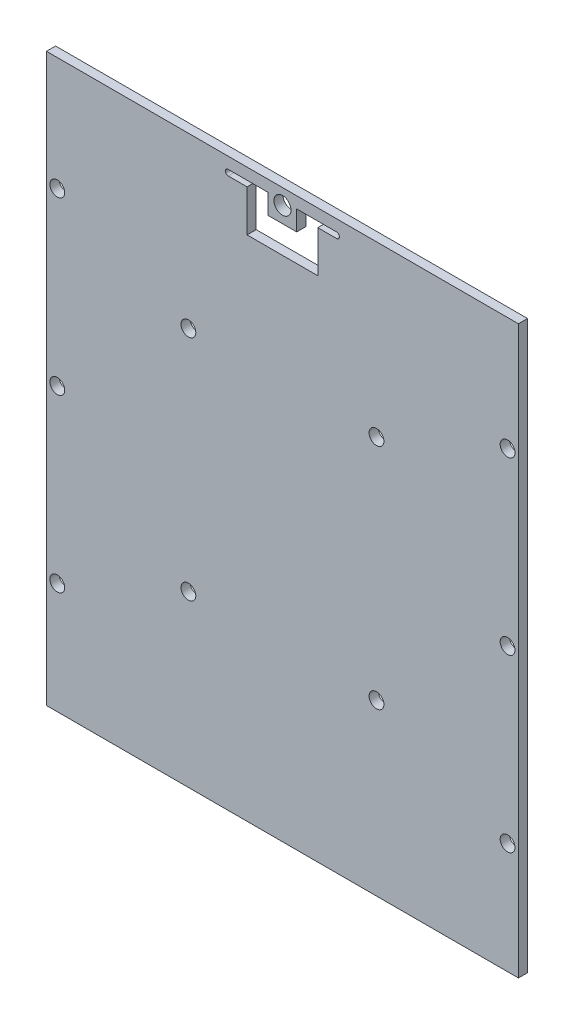
SolidWorks part; units mm, degrees
material "FR4_stuffedProtoboard"
ref_plane "Front Plane" through (0, 0, 0) normal (0, 0, 1) x (1, 0, 0)
ref_plane "Top Plane" through (0, 0, 0) normal (0, 1, 0) x (1, 0, 0)
ref_plane "Right Plane" through (0, 0, 0) normal (1, 0, 0) x (0, 0, -1)
sketch "Sketch1" plane through (0, 0, 0) normal (0, 0, 1) x (1, 0, 0)
  line L0 (-37, -97) -> (37, -97) construction
  line L5 (-37, -95.4) -> (37, -95.4) construction
  line L6 (-37, -87) -> (37, -87) construction
  line L7 (-37, -85.4) -> (37, -85.4) construction
  line L8 (-37, -77) -> (37, -77) construction
  line L9 (-37, -75.4) -> (37, -75.4) construction
  line L10 (-37, -67) -> (37, -67) construction
  line L11 (-37, -65.4) -> (37, -65.4) construction
  line L12 (-37, -57) -> (37, -57) construction
  line L13 (-37, -55.4) -> (37, -55.4) construction
  line L14 (-37, -47) -> (37, -47) construction
  line L15 (-37, -45.4) -> (37, -45.4) construction
  line L16 (-37, -37) -> (37, -37) construction
  line L17 (-37, -35.4) -> (37, -35.4) construction
  line L18 (-37, -27) -> (37, -27) construction
  line L19 (-37, -25.4) -> (37, -25.4) construction
  line L20 (-37, -17) -> (37, -17) construction
  line L21 (-37, -15.4) -> (37, -15.4) construction
  line L22 (-37, 15.4) -> (37, 15.4) construction
  line L23 (-37, 17) -> (37, 17) construction
  line L24 (-37, 25.4) -> (37, 25.4) construction
  line L25 (-37, 27) -> (37, 27) construction
  line L26 (-37, 35.4) -> (37, 35.4) construction
  line L27 (-37, 37) -> (37, 37) construction
  line L29 (-41.5, 107) -> (41.5, 107)
  line L30 (-41.5, 107) -> (-41.5, -107)
  line L31 (-41.5, -107) -> (41.5, -107)
  line L33 (41.5, 107) -> (41.5, -107)
  line L35 (-26.7, 107) -> (-28.3, 107) construction
  line L37 (-41.5, 109.5) -> (-41.5, 97.4) construction
  line L38 (41.5, 112.5) -> (41.5, 109.5) construction
  line L39 (-28.3, -107) -> (-26.7, -107) construction
  line L40 (-41.4, 106.9) -> (41.4, 106.9)
  line L41 (41.4, 106.9) -> (41.4, -106.9)
  line L42 (-41.4, -106.9) -> (41.4, -106.9)
  line L43 (-41.4, 106.9) -> (-41.4, -106.9)
  line L76 (-37, 45.4) -> (37, 45.4) construction
  line L77 (-37, 47) -> (37, 47) construction
  line L78 (-37, 55.4) -> (37, 55.4) construction
  line L79 (-37, 57) -> (37, 57) construction
  line L80 (-37, 65.4) -> (37, 65.4) construction
  line L81 (-37, 67) -> (37, 67) construction
  line L82 (-37, 75.4) -> (37, 75.4) construction
  line L83 (-37, 77) -> (37, 77) construction
  line L84 (-37, 85.4) -> (37, 85.4) construction
  line L85 (-37, 87) -> (37, 87) construction
  line L86 (-37, 95.4) -> (37, 95.4) construction
  line L87 (-37, 97) -> (37, 97) construction
  line L88 (-37, -97) -> (37, -97) construction
  line L89 (-37, -95.4) -> (37, -95.4) construction
  line L90 (-37, -87) -> (37, -87) construction
  line L91 (-37, -85.4) -> (37, -85.4) construction
  line L92 (-37, -77) -> (37, -77) construction
  line L93 (-37, -75.4) -> (37, -75.4) construction
  line L94 (-37, -67) -> (37, -67) construction
  line L95 (-37, -65.4) -> (37, -65.4) construction
  line L96 (-37, -57) -> (37, -57) construction
  line L97 (-37, -55.4) -> (37, -55.4) construction
  line L98 (-37, -47) -> (37, -47) construction
  line L99 (-37, -45.4) -> (37, -45.4) construction
  line L100 (-37, -37) -> (37, -37) construction
  line L101 (-37, -35.4) -> (37, -35.4) construction
  line L102 (-37, -27) -> (37, -27) construction
  line L103 (-37, -25.4) -> (37, -25.4) construction
  line L104 (-37, -17) -> (37, -17) construction
  line L105 (-37, -15.4) -> (37, -15.4) construction
  line L106 (-37, 15.4) -> (37, 15.4) construction
  line L107 (-37, 17) -> (37, 17) construction
  line L108 (-37, 25.4) -> (37, 25.4) construction
  line L109 (-37, 27) -> (37, 27) construction
  line L110 (-37, 35.4) -> (37, 35.4) construction
  line L111 (-37, 37) -> (37, 37) construction
  line L112 (-37, 45.4) -> (37, 45.4) construction
  line L113 (-37, 47) -> (37, 47) construction
  line L114 (-37, 55.4) -> (37, 55.4) construction
  line L115 (-37, 57) -> (37, 57) construction
  line L116 (-37, 65.4) -> (37, 65.4) construction
  line L117 (-37, 67) -> (37, 67) construction
  line L118 (-37, 75.4) -> (37, 75.4) construction
  line L119 (-37, 77) -> (37, 77) construction
  line L120 (-37, 85.4) -> (37, 85.4) construction
  line L121 (-37, 87) -> (37, 87) construction
  line L122 (-37, 95.4) -> (37, 95.4) construction
  line L123 (-37, 97) -> (37, 97) construction
  circle A0 centre (-39.5, 87) radius 0.8 construction
  circle A1 centre (-39.5, -27) radius 0.8 construction
  circle A2 centre (-39.5, 57) radius 0.8 construction
  circle A3 centre (39.5, -27) radius 0.8 construction
  circle A4 centre (-39.5, -27) radius 0.8
  circle A5 centre (-39.5, 27) radius 0.8 construction
  circle A8 centre (39.5, -27) radius 0.8
  circle A11 centre (-39.5, -57) radius 0.8 construction
  circle A13 centre (-39.5, -87) radius 0.8 construction
  circle A16 centre (0, -104.2) radius 0.8 construction
  circle A19 centre (39.5, -87) radius 0.8 construction
  circle A21 centre (39.5, -57) radius 0.8 construction
  circle A27 centre (39.5, 27) radius 0.8 construction
  circle A30 centre (39.5, 57) radius 0.8 construction
  circle A32 centre (39.5, 87) radius 0.8 construction
  circle A35 centre (0, 104.2) radius 0.8 construction
  circle A38 centre (-39.5, 87) radius 0.8
  circle A40 centre (-39.5, 57) radius 0.8
  circle A43 centre (-39.5, 27) radius 0.8
  circle A49 centre (-39.5, -57) radius 0.8
  circle A51 centre (-39.5, -87) radius 0.8
  circle A54 centre (0, -104.2) radius 0.8
  circle A57 centre (39.5, -87) radius 0.8
  circle A59 centre (39.5, -57) radius 0.8
  circle A65 centre (39.5, 27) radius 0.8
  circle A68 centre (39.5, 57) radius 0.8
  circle A70 centre (39.5, 87) radius 0.8
  circle A73 centre (0, 104.2) radius 0.8
  dimension "D1" = 0.1
extrude "pcb extrude" add sketch "Sketch1" along normal blind 1.6
sketch "Sketch7" plane through (0, 0, 1.6) normal (0, 0, 1) x (1, 0, 0)
  line L0 (-41.4, 106.9) -> (41.4, 106.9) construction
  line L1 (-41.25, 106.9) -> (-41.4, 106.9)
  line L2 (-41.25, 106.75) -> (-41.25, -106.75)
  line L3 (-41.25, -106.9) -> (-41.4, -106.9)
  line L4 (-41.4, 106.9) -> (-41.4, -106.9)
  line L5 (-41.4, -106.9) -> (41.4, -106.9) construction
  line L6 (-41.4, 106.9) -> (-41.4, -106.9) construction
  line L7 (0, -55) -> (0, 55) construction
  line L8 (41.25, -106.9) -> (41.4, -106.9)
  line L9 (41.4, 106.9) -> (41.4, -106.9)
  line L10 (41.25, 106.9) -> (41.4, 106.9)
  line L11 (41.25, 106.75) -> (41.25, -106.75)
  line L12 (55, 0) -> (-55, 0) construction
  line L13 (-41.25, -106.9) -> (41.25, -106.9)
  line L15 (-41.25, -106.75) -> (41.25, -106.75)
  line L17 (-41.25, 106.75) -> (41.25, 106.75)
  line L19 (-41.25, 106.9) -> (41.25, 106.9)
  dimension "D1" = 0.15
  dimension "D2" = 0.15
  dimension "D3" = 0.15
  dimension "D4" = 0.15
extrude "Offset Edges" [suppressed] cut sketch "Sketch7" against normal up to surface (1.6 mm away)
sketch "connector locations" plane through (0, 0, 1.6) normal (0, 0, 1) x (1, 0, 0)
  line L0 (-37, 97) -> (37, 97) construction
  line L1 (-33.9182, 100.556) -> (-9.2802, 100.556)
  line L2 (-33.9182, 100.556) -> (-33.9182, 99.159)
  line L3 (-33.9182, 99.159) -> (-9.2802, 99.159)
  line L4 (-9.2802, 100.556) -> (-9.2802, 99.159)
  line L5 (-33.9182, 100.556) -> (-9.2802, 99.159) construction
  line L6 (-33.9182, 99.159) -> (-9.2802, 100.556) construction
  line L7 (-37, 87) -> (37, 87) construction
  line L8 (-33.9182, 90.556) -> (-22.0818, 90.556)
  line L9 (-33.9182, 90.556) -> (-33.9182, 89.159)
  line L10 (-33.9182, 89.159) -> (-22.0818, 89.159)
  line L11 (-22.0818, 90.556) -> (-22.0818, 89.159)
  line L12 (-33.9182, 90.556) -> (-22.0818, 89.159) construction
  line L13 (-33.9182, 89.159) -> (-22.0818, 90.556) construction
  line L14 (0, -0.88) -> (0, 0.88) construction
  line L15 (-12.319, 90.556) -> (12.319, 90.556)
  line L16 (-12.319, 90.556) -> (-12.319, 89.159)
  line L17 (-12.319, 89.159) -> (12.319, 89.159)
  line L18 (12.319, 90.556) -> (12.319, 89.159)
  line L19 (-12.319, 90.556) -> (12.319, 89.159) construction
  line L20 (-12.319, 89.159) -> (12.319, 90.556) construction
  line L21 (-37, -85.4) -> (37, -85.4) construction
  line L22 (-33.9182, -91.844) -> (-9.2802, -91.844)
  line L23 (-33.9182, -91.844) -> (-33.9182, -93.241)
  line L24 (-33.9182, -93.241) -> (-9.2802, -93.241)
  line L25 (-9.2802, -91.844) -> (-9.2802, -93.241)
  line L26 (-33.9182, -91.844) -> (-9.2802, -93.241) construction
  line L27 (-33.9182, -93.241) -> (-9.2802, -91.844) construction
  line L28 (-33.9182, -81.844) -> (-22.0818, -81.844)
  line L29 (-33.9182, -81.844) -> (-33.9182, -83.241)
  line L30 (-33.9182, -83.241) -> (-22.0818, -83.241)
  line L31 (-22.0818, -81.844) -> (-22.0818, -83.241)
  line L32 (-33.9182, -81.844) -> (-22.0818, -83.241) construction
  line L33 (-33.9182, -83.241) -> (-22.0818, -81.844) construction
  line L34 (-12.319, -81.844) -> (12.319, -81.844)
  line L35 (-12.319, -81.844) -> (-12.319, -83.241)
  line L36 (-12.319, -83.241) -> (12.319, -83.241)
  line L37 (12.319, -81.844) -> (12.319, -83.241)
  line L38 (-12.319, -81.844) -> (12.319, -83.241) construction
  line L39 (-12.319, -83.241) -> (12.319, -81.844) construction
  line L40 (-37, -95.4) -> (37, -95.4) construction
  line L41 (-33.9182, 80.556) -> (-33.9182, 79.159)
  line L42 (-33.9182, 80.556) -> (-22.0818, 80.556)
  line L43 (-22.0818, 80.556) -> (-22.0818, 79.159)
  line L44 (-33.9182, 79.159) -> (-22.0818, 79.159)
  line L45 (-33.9182, 80.556) -> (-22.0818, 79.159) construction
  line L46 (-33.9182, 79.159) -> (-22.0818, 80.556) construction
  line L47 (-12.319, 80.556) -> (-12.319, 79.159)
  line L48 (-12.319, 80.556) -> (12.319, 80.556)
  line L49 (12.319, 80.556) -> (12.319, 79.159)
  line L50 (-12.319, 79.159) -> (12.319, 79.159)
  line L51 (-12.319, 80.556) -> (12.319, 79.159) construction
  line L52 (-12.319, 79.159) -> (12.319, 80.556) construction
  line L53 (-33.9182, 70.556) -> (-33.9182, 69.159)
  line L54 (-33.9182, 70.556) -> (-22.0818, 70.556)
  line L55 (-22.0818, 70.556) -> (-22.0818, 69.159)
  line L56 (-33.9182, 69.159) -> (-22.0818, 69.159)
  line L57 (-33.9182, 70.556) -> (-22.0818, 69.159) construction
  line L58 (-33.9182, 69.159) -> (-22.0818, 70.556) construction
  line L59 (-12.319, 70.556) -> (-12.319, 69.159)
  line L60 (-12.319, 70.556) -> (12.319, 70.556)
  line L61 (12.319, 70.556) -> (12.319, 69.159)
  line L62 (-12.319, 69.159) -> (12.319, 69.159)
  line L63 (-12.319, 70.556) -> (12.319, 69.159) construction
  line L64 (-12.319, 69.159) -> (12.319, 70.556) construction
  line L65 (-33.9182, 60.556) -> (-33.9182, 59.159)
  line L66 (-33.9182, 60.556) -> (-22.0818, 60.556)
  line L67 (-22.0818, 60.556) -> (-22.0818, 59.159)
  line L68 (-33.9182, 59.159) -> (-22.0818, 59.159)
  line L69 (-33.9182, 60.556) -> (-22.0818, 59.159) construction
  line L70 (-33.9182, 59.159) -> (-22.0818, 60.556) construction
  line L71 (-12.319, 60.556) -> (-12.319, 59.159)
  line L72 (-12.319, 60.556) -> (12.319, 60.556)
  line L73 (12.319, 60.556) -> (12.319, 59.159)
  line L74 (-12.319, 59.159) -> (12.319, 59.159)
  line L75 (-12.319, 60.556) -> (12.319, 59.159) construction
  line L76 (-12.319, 59.159) -> (12.319, 60.556) construction
  line L77 (-33.9182, 50.556) -> (-33.9182, 49.159)
  line L78 (-33.9182, 50.556) -> (-22.0818, 50.556)
  line L79 (-22.0818, 50.556) -> (-22.0818, 49.159)
  line L80 (-33.9182, 49.159) -> (-22.0818, 49.159)
  line L81 (-33.9182, 50.556) -> (-22.0818, 49.159) construction
  line L82 (-33.9182, 49.159) -> (-22.0818, 50.556) construction
  line L83 (-12.319, 50.556) -> (-12.319, 49.159)
  line L84 (-12.319, 50.556) -> (12.319, 50.556)
  line L85 (12.319, 50.556) -> (12.319, 49.159)
  line L86 (-12.319, 49.159) -> (12.319, 49.159)
  line L87 (-12.319, 50.556) -> (12.319, 49.159) construction
  line L88 (-12.319, 49.159) -> (12.319, 50.556) construction
  line L89 (-33.9182, 40.556) -> (-33.9182, 39.159)
  line L90 (-33.9182, 40.556) -> (-22.0818, 40.556)
  line L91 (-22.0818, 40.556) -> (-22.0818, 39.159)
  line L92 (-33.9182, 39.159) -> (-22.0818, 39.159)
  line L93 (-33.9182, 40.556) -> (-22.0818, 39.159) construction
  line L94 (-33.9182, 39.159) -> (-22.0818, 40.556) construction
  line L95 (-12.319, 40.556) -> (-12.319, 39.159)
  line L96 (-12.319, 40.556) -> (12.319, 40.556)
  line L97 (12.319, 40.556) -> (12.319, 39.159)
  line L98 (-12.319, 39.159) -> (12.319, 39.159)
  line L99 (-12.319, 40.556) -> (12.319, 39.159) construction
  line L100 (-12.319, 39.159) -> (12.319, 40.556) construction
  line L101 (-33.9182, 30.556) -> (-33.9182, 29.159)
  line L102 (-33.9182, 30.556) -> (-22.0818, 30.556)
  line L103 (-22.0818, 30.556) -> (-22.0818, 29.159)
  line L104 (-33.9182, 29.159) -> (-22.0818, 29.159)
  line L105 (-33.9182, 30.556) -> (-22.0818, 29.159) construction
  line L106 (-33.9182, 29.159) -> (-22.0818, 30.556) construction
  line L107 (-12.319, 30.556) -> (-12.319, 29.159)
  line L108 (-12.319, 30.556) -> (12.319, 30.556)
  line L109 (12.319, 30.556) -> (12.319, 29.159)
  line L110 (-12.319, 29.159) -> (12.319, 29.159)
  line L111 (-12.319, 30.556) -> (12.319, 29.159) construction
  line L112 (-12.319, 29.159) -> (12.319, 30.556) construction
  line L113 (-33.9182, 20.556) -> (-33.9182, 19.159)
  line L114 (-33.9182, 20.556) -> (-22.0818, 20.556)
  line L115 (-22.0818, 20.556) -> (-22.0818, 19.159)
  line L116 (-33.9182, 19.159) -> (-22.0818, 19.159)
  line L117 (-33.9182, 20.556) -> (-22.0818, 19.159) construction
  line L118 (-33.9182, 19.159) -> (-22.0818, 20.556) construction
  line L119 (-12.319, 20.556) -> (-12.319, 19.159)
  line L120 (-12.319, 20.556) -> (12.319, 20.556)
  line L121 (12.319, 20.556) -> (12.319, 19.159)
  line L122 (-12.319, 19.159) -> (12.319, 19.159)
  line L123 (-12.319, 20.556) -> (12.319, 19.159) construction
  line L124 (-12.319, 19.159) -> (12.319, 20.556) construction
  line L125 (-33.9182, 10.556) -> (-33.9182, 9.159)
  line L126 (-33.9182, 10.556) -> (-22.0818, 10.556)
  line L127 (-22.0818, 10.556) -> (-22.0818, 9.159)
  line L128 (-33.9182, 9.159) -> (-22.0818, 9.159)
  line L129 (-33.9182, 10.556) -> (-22.0818, 9.159) construction
  line L130 (-33.9182, 9.159) -> (-22.0818, 10.556) construction
  line L131 (-12.319, 10.556) -> (-12.319, 9.159)
  line L132 (-12.319, 10.556) -> (12.319, 10.556)
  line L133 (12.319, 10.556) -> (12.319, 9.159)
  line L134 (-12.319, 9.159) -> (12.319, 9.159)
  line L135 (-12.319, 10.556) -> (12.319, 9.159) construction
  line L136 (-12.319, 9.159) -> (12.319, 10.556) construction
  line L137 (0, 89.8575) -> (0, 79.8575) construction
  line L138 (-33.9182, -71.844) -> (-33.9182, -73.241)
  line L139 (-33.9182, -71.844) -> (-22.0818, -71.844)
  line L140 (-22.0818, -71.844) -> (-22.0818, -73.241)
  line L141 (-33.9182, -73.241) -> (-22.0818, -73.241)
  line L142 (-33.9182, -73.241) -> (-22.0818, -71.844) construction
  line L143 (-33.9182, -71.844) -> (-22.0818, -73.241) construction
  line L144 (-12.319, -71.844) -> (-12.319, -73.241)
  line L145 (-12.319, -71.844) -> (12.319, -71.844)
  line L146 (12.319, -71.844) -> (12.319, -73.241)
  line L147 (-12.319, -73.241) -> (12.319, -73.241)
  line L148 (-12.319, -73.241) -> (12.319, -71.844) construction
  line L149 (-12.319, -71.844) -> (12.319, -73.241) construction
  line L150 (-33.9182, -61.844) -> (-33.9182, -63.241)
  line L151 (-33.9182, -61.844) -> (-22.0818, -61.844)
  line L152 (-22.0818, -61.844) -> (-22.0818, -63.241)
  line L153 (-33.9182, -63.241) -> (-22.0818, -63.241)
  line L154 (-33.9182, -63.241) -> (-22.0818, -61.844) construction
  line L155 (-33.9182, -61.844) -> (-22.0818, -63.241) construction
  line L156 (-12.319, -61.844) -> (-12.319, -63.241)
  line L157 (-12.319, -61.844) -> (12.319, -61.844)
  line L158 (12.319, -61.844) -> (12.319, -63.241)
  line L159 (-12.319, -63.241) -> (12.319, -63.241)
  line L160 (-12.319, -63.241) -> (12.319, -61.844) construction
  line L161 (-12.319, -61.844) -> (12.319, -63.241) construction
  line L162 (-33.9182, -51.844) -> (-33.9182, -53.241)
  line L163 (-33.9182, -51.844) -> (-22.0818, -51.844)
  line L164 (-22.0818, -51.844) -> (-22.0818, -53.241)
  line L165 (-33.9182, -53.241) -> (-22.0818, -53.241)
  line L166 (-33.9182, -53.241) -> (-22.0818, -51.844) construction
  line L167 (-33.9182, -51.844) -> (-22.0818, -53.241) construction
  line L168 (-12.319, -51.844) -> (-12.319, -53.241)
  line L169 (-12.319, -51.844) -> (12.319, -51.844)
  line L170 (12.319, -51.844) -> (12.319, -53.241)
  line L171 (-12.319, -53.241) -> (12.319, -53.241)
  line L172 (-12.319, -53.241) -> (12.319, -51.844) construction
  line L173 (-12.319, -51.844) -> (12.319, -53.241) construction
  line L174 (-33.9182, -41.844) -> (-33.9182, -43.241)
  line L175 (-33.9182, -41.844) -> (-22.0818, -41.844)
  line L176 (-22.0818, -41.844) -> (-22.0818, -43.241)
  line L177 (-33.9182, -43.241) -> (-22.0818, -43.241)
  line L178 (-33.9182, -43.241) -> (-22.0818, -41.844) construction
  line L179 (-33.9182, -41.844) -> (-22.0818, -43.241) construction
  line L180 (-12.319, -41.844) -> (-12.319, -43.241)
  line L181 (-12.319, -41.844) -> (12.319, -41.844)
  line L182 (12.319, -41.844) -> (12.319, -43.241)
  line L183 (-12.319, -43.241) -> (12.319, -43.241)
  line L184 (-12.319, -43.241) -> (12.319, -41.844) construction
  line L185 (-12.319, -41.844) -> (12.319, -43.241) construction
  line L186 (-33.9182, -31.844) -> (-33.9182, -33.241)
  line L187 (-33.9182, -31.844) -> (-22.0818, -31.844)
  line L188 (-22.0818, -31.844) -> (-22.0818, -33.241)
  line L189 (-33.9182, -33.241) -> (-22.0818, -33.241)
  line L190 (-33.9182, -33.241) -> (-22.0818, -31.844) construction
  line L191 (-33.9182, -31.844) -> (-22.0818, -33.241) construction
  line L192 (-12.319, -31.844) -> (-12.319, -33.241)
  line L193 (-12.319, -31.844) -> (12.319, -31.844)
  line L194 (12.319, -31.844) -> (12.319, -33.241)
  line L195 (-12.319, -33.241) -> (12.319, -33.241)
  line L196 (-12.319, -33.241) -> (12.319, -31.844) construction
  line L197 (-12.319, -31.844) -> (12.319, -33.241) construction
  line L198 (-33.9182, -21.844) -> (-33.9182, -23.241)
  line L199 (-33.9182, -21.844) -> (-22.0818, -21.844)
  line L200 (-22.0818, -21.844) -> (-22.0818, -23.241)
  line L201 (-33.9182, -23.241) -> (-22.0818, -23.241)
  line L202 (-33.9182, -23.241) -> (-22.0818, -21.844) construction
  line L203 (-33.9182, -21.844) -> (-22.0818, -23.241) construction
  line L204 (-12.319, -21.844) -> (-12.319, -23.241)
  line L205 (-12.319, -21.844) -> (12.319, -21.844)
  line L206 (12.319, -21.844) -> (12.319, -23.241)
  line L207 (-12.319, -23.241) -> (12.319, -23.241)
  line L208 (-12.319, -23.241) -> (12.319, -21.844) construction
  line L209 (-12.319, -21.844) -> (12.319, -23.241) construction
  line L210 (-33.9182, -11.844) -> (-33.9182, -13.241)
  line L211 (-33.9182, -11.844) -> (-22.0818, -11.844)
  line L212 (-22.0818, -11.844) -> (-22.0818, -13.241)
  line L213 (-33.9182, -13.241) -> (-22.0818, -13.241)
  line L214 (-33.9182, -13.241) -> (-22.0818, -11.844) construction
  line L215 (-33.9182, -11.844) -> (-22.0818, -13.241) construction
  line L216 (-12.319, -11.844) -> (-12.319, -13.241)
  line L217 (-12.319, -11.844) -> (12.319, -11.844)
  line L218 (12.319, -11.844) -> (12.319, -13.241)
  line L219 (-12.319, -13.241) -> (12.319, -13.241)
  line L220 (-12.319, -13.241) -> (12.319, -11.844) construction
  line L221 (-12.319, -11.844) -> (12.319, -13.241) construction
  line L222 (-33.9182, -1.844) -> (-33.9182, -3.241)
  line L223 (-33.9182, -1.844) -> (-22.0818, -1.844)
  line L224 (-22.0818, -1.844) -> (-22.0818, -3.241)
  line L225 (-33.9182, -3.241) -> (-22.0818, -3.241)
  line L226 (-33.9182, -3.241) -> (-22.0818, -1.844) construction
  line L227 (-33.9182, -1.844) -> (-22.0818, -3.241) construction
  line L228 (-12.319, -1.844) -> (-12.319, -3.241)
  line L229 (-12.319, -1.844) -> (12.319, -1.844)
  line L230 (12.319, -1.844) -> (12.319, -3.241)
  line L231 (-12.319, -3.241) -> (12.319, -3.241)
  line L232 (-12.319, -3.241) -> (12.319, -1.844) construction
  line L233 (-12.319, -1.844) -> (12.319, -3.241) construction
  line L234 (0, -82.5425) -> (0, -72.5425) construction
  line L235 (26.92, 96.09) -> (29.08, 98.27) construction
  line L236 (26.92, 98.27) -> (29.08, 96.09) construction
  line L237 (32.92, 98.27) -> (35.08, 96.09) construction
  line L238 (32.92, 96.09) -> (35.08, 98.27) construction
  line L239 (20.92, 96.09) -> (23.08, 98.27) construction
  line L240 (20.92, 98.27) -> (23.08, 96.09) construction
  line L241 (26.92, 86.09) -> (29.08, 88.27) construction
  line L242 (26.92, 88.27) -> (29.08, 86.09) construction
  line L243 (20.92, 86.09) -> (23.08, 88.27) construction
  line L244 (20.92, 88.27) -> (23.08, 86.09) construction
  line L245 (26.92, 76.09) -> (29.08, 78.27) construction
  line L246 (26.92, 78.27) -> (29.08, 76.09) construction
  line L247 (20.92, 76.09) -> (23.08, 78.27) construction
  line L248 (20.92, 78.27) -> (23.08, 76.09) construction
  line L249 (26.92, 66.09) -> (29.08, 68.27) construction
  line L250 (26.92, 68.27) -> (29.08, 66.09) construction
  line L251 (20.92, 66.09) -> (23.08, 68.27) construction
  line L252 (20.92, 68.27) -> (23.08, 66.09) construction
  line L253 (26.92, 56.09) -> (29.08, 58.27) construction
  line L254 (26.92, 58.27) -> (29.08, 56.09) construction
  line L255 (20.92, 56.09) -> (23.08, 58.27) construction
  line L256 (20.92, 58.27) -> (23.08, 56.09) construction
  line L257 (26.92, 46.09) -> (29.08, 48.27) construction
  line L258 (26.92, 48.27) -> (29.08, 46.09) construction
  line L259 (20.92, 46.09) -> (23.08, 48.27) construction
  line L260 (20.92, 48.27) -> (23.08, 46.09) construction
  line L261 (26.92, 36.09) -> (29.08, 38.27) construction
  line L262 (26.92, 38.27) -> (29.08, 36.09) construction
  line L263 (20.92, 36.09) -> (23.08, 38.27) construction
  line L264 (20.92, 38.27) -> (23.08, 36.09) construction
  line L265 (26.92, 26.09) -> (29.08, 28.27) construction
  line L266 (26.92, 28.27) -> (29.08, 26.09) construction
  line L267 (20.92, 26.09) -> (23.08, 28.27) construction
  line L268 (20.92, 28.27) -> (23.08, 26.09) construction
  line L269 (26.92, 16.09) -> (29.08, 18.27) construction
  line L270 (26.92, 18.27) -> (29.08, 16.09) construction
  line L271 (20.92, 16.09) -> (23.08, 18.27) construction
  line L272 (20.92, 18.27) -> (23.08, 16.09) construction
  line L273 (26.92, 6.09) -> (29.08, 8.27) construction
  line L274 (26.92, 8.27) -> (29.08, 6.09) construction
  line L275 (20.92, 6.09) -> (23.08, 8.27) construction
  line L276 (20.92, 8.27) -> (23.08, 6.09) construction
  line L277 (32.92, 86.09) -> (35.08, 88.27) construction
  line L278 (32.92, 88.27) -> (35.08, 86.09) construction
  line L279 (32.92, 76.09) -> (35.08, 78.27) construction
  line L280 (32.92, 78.27) -> (35.08, 76.09) construction
  line L281 (32.92, 66.09) -> (35.08, 68.27) construction
  line L282 (32.92, 68.27) -> (35.08, 66.09) construction
  line L283 (32.92, 56.09) -> (35.08, 58.27) construction
  line L284 (32.92, 58.27) -> (35.08, 56.09) construction
  line L285 (32.92, 46.09) -> (35.08, 48.27) construction
  line L286 (32.92, 48.27) -> (35.08, 46.09) construction
  line L287 (32.92, 36.09) -> (35.08, 38.27) construction
  line L288 (32.92, 38.27) -> (35.08, 36.09) construction
  line L289 (32.92, 26.09) -> (35.08, 28.27) construction
  line L290 (32.92, 28.27) -> (35.08, 26.09) construction
  line L291 (32.92, 16.09) -> (35.08, 18.27) construction
  line L292 (32.92, 18.27) -> (35.08, 16.09) construction
  line L293 (32.92, 6.09) -> (35.08, 8.27) construction
  line L294 (32.92, 8.27) -> (35.08, 6.09) construction
  line L295 (32.92, 98.27) -> (26.92, 98.27) construction
  line L296 (32.92, 98.27) -> (32.92, 88.27) construction
  line L297 (32.92, -94.13) -> (35.08, -96.31) construction
  line L298 (35.08, -94.13) -> (32.92, -96.31) construction
  line L299 (29.08, -94.13) -> (26.92, -96.31) construction
  line L300 (26.92, -94.13) -> (29.08, -96.31) construction
  line L301 (23.08, -94.13) -> (20.92, -96.31) construction
  line L302 (20.92, -94.13) -> (23.08, -96.31) construction
  line L303 (29.08, -84.13) -> (26.92, -86.31) construction
  line L304 (26.92, -84.13) -> (29.08, -86.31) construction
  line L305 (23.08, -84.13) -> (20.92, -86.31) construction
  line L306 (20.92, -84.13) -> (23.08, -86.31) construction
  line L307 (29.08, -74.13) -> (26.92, -76.31) construction
  line L308 (26.92, -74.13) -> (29.08, -76.31) construction
  line L309 (23.08, -74.13) -> (20.92, -76.31) construction
  line L310 (20.92, -74.13) -> (23.08, -76.31) construction
  line L311 (29.08, -64.13) -> (26.92, -66.31) construction
  line L312 (26.92, -64.13) -> (29.08, -66.31) construction
  line L313 (23.08, -64.13) -> (20.92, -66.31) construction
  line L314 (20.92, -64.13) -> (23.08, -66.31) construction
  line L315 (29.08, -54.13) -> (26.92, -56.31) construction
  line L316 (26.92, -54.13) -> (29.08, -56.31) construction
  line L317 (23.08, -54.13) -> (20.92, -56.31) construction
  line L318 (20.92, -54.13) -> (23.08, -56.31) construction
  line L319 (29.08, -44.13) -> (26.92, -46.31) construction
  line L320 (26.92, -44.13) -> (29.08, -46.31) construction
  line L321 (23.08, -44.13) -> (20.92, -46.31) construction
  line L322 (20.92, -44.13) -> (23.08, -46.31) construction
  line L323 (29.08, -34.13) -> (26.92, -36.31) construction
  line L324 (26.92, -34.13) -> (29.08, -36.31) construction
  line L325 (23.08, -34.13) -> (20.92, -36.31) construction
  line L326 (20.92, -34.13) -> (23.08, -36.31) construction
  line L327 (29.08, -24.13) -> (26.92, -26.31) construction
  line L328 (26.92, -24.13) -> (29.08, -26.31) construction
  line L329 (23.08, -24.13) -> (20.92, -26.31) construction
  line L330 (20.92, -24.13) -> (23.08, -26.31) construction
  line L331 (29.08, -14.13) -> (26.92, -16.31) construction
  line L332 (26.92, -14.13) -> (29.08, -16.31) construction
  line L333 (23.08, -14.13) -> (20.92, -16.31) construction
  line L334 (20.92, -14.13) -> (23.08, -16.31) construction
  line L335 (29.08, -4.13) -> (26.92, -6.31) construction
  line L336 (26.92, -4.13) -> (29.08, -6.31) construction
  line L337 (23.08, -4.13) -> (20.92, -6.31) construction
  line L338 (20.92, -4.13) -> (23.08, -6.31) construction
  line L339 (35.08, -84.13) -> (32.92, -86.31) construction
  line L340 (32.92, -84.13) -> (35.08, -86.31) construction
  line L341 (35.08, -74.13) -> (32.92, -76.31) construction
  line L342 (32.92, -74.13) -> (35.08, -76.31) construction
  line L343 (35.08, -64.13) -> (32.92, -66.31) construction
  line L344 (32.92, -64.13) -> (35.08, -66.31) construction
  line L345 (35.08, -54.13) -> (32.92, -56.31) construction
  line L346 (32.92, -54.13) -> (35.08, -56.31) construction
  line L347 (35.08, -44.13) -> (32.92, -46.31) construction
  line L348 (32.92, -44.13) -> (35.08, -46.31) construction
  line L349 (35.08, -34.13) -> (32.92, -36.31) construction
  line L350 (32.92, -34.13) -> (35.08, -36.31) construction
  line L351 (35.08, -24.13) -> (32.92, -26.31) construction
  line L352 (32.92, -24.13) -> (35.08, -26.31) construction
  line L353 (35.08, -14.13) -> (32.92, -16.31) construction
  line L354 (32.92, -14.13) -> (35.08, -16.31) construction
  line L355 (35.08, -4.13) -> (32.92, -6.31) construction
  line L356 (32.92, -4.13) -> (35.08, -6.31) construction
  line L357 (32.92, -94.13) -> (26.92, -94.13) construction
  line L358 (32.92, -94.13) -> (32.92, -84.13) construction
  line L359 (-28, 89.8575) -> (-28, 79.8575) construction
  line L360 (-28, -82.5425) -> (-28, -72.5425) construction
  line L361 (-37, 100.5) -> (-37, -100.5) construction
  line L362 (-34.5, -103) -> (-4.5, -103) construction
  line L363 (-2.5, -102) -> (2.5, -102) construction
  line L364 (4.5, -103) -> (34.5, -103) construction
  line L365 (37, -100.5) -> (37, 100.5) construction
  line L366 (34.5, 103) -> (4.5, 103) construction
  line L367 (-2.5, 102) -> (2.5, 102) construction
  line L368 (-4.5, 103) -> (-34.5, 103) construction
  line L369 (-37, 100.5) -> (-37, -100.5)
  line L370 (-34.5, -103) -> (-4.5, -103)
  line L371 (-2.5, -102) -> (2.5, -102)
  line L372 (4.5, -103) -> (34.5, -103)
  line L373 (37, -100.5) -> (37, 100.5)
  line L374 (34.5, 103) -> (4.5, 103)
  line L375 (-2.5, 102) -> (2.5, 102)
  line L376 (-4.5, 103) -> (-34.5, 103)
  circle A0 centre (32.92, 98.27) radius 0.32
  circle A1 centre (35.08, 98.27) radius 0.32
  circle A2 centre (35.08, 96.09) radius 0.32
  circle A3 centre (32.92, 96.09) radius 0.32
  circle A4 centre (26.92, 98.27) radius 0.32
  circle A5 centre (29.08, 98.27) radius 0.32
  circle A6 centre (29.08, 96.09) radius 0.32
  circle A7 centre (26.92, 96.09) radius 0.32
  circle A8 centre (20.92, 98.27) radius 0.32
  circle A9 centre (23.08, 98.27) radius 0.32
  circle A10 centre (23.08, 96.09) radius 0.32
  circle A11 centre (20.92, 96.09) radius 0.32
  circle A12 centre (26.92, 88.27) radius 0.32
  circle A13 centre (29.08, 88.27) radius 0.32
  circle A14 centre (29.08, 86.09) radius 0.32
  circle A15 centre (26.92, 86.09) radius 0.32
  circle A16 centre (20.92, 88.27) radius 0.32
  circle A17 centre (23.08, 88.27) radius 0.32
  circle A18 centre (23.08, 86.09) radius 0.32
  circle A19 centre (20.92, 86.09) radius 0.32
  circle A20 centre (26.92, 78.27) radius 0.32
  circle A21 centre (29.08, 78.27) radius 0.32
  circle A22 centre (29.08, 76.09) radius 0.32
  circle A23 centre (26.92, 76.09) radius 0.32
  circle A24 centre (20.92, 78.27) radius 0.32
  circle A25 centre (23.08, 78.27) radius 0.32
  circle A26 centre (23.08, 76.09) radius 0.32
  circle A27 centre (20.92, 76.09) radius 0.32
  circle A28 centre (26.92, 68.27) radius 0.32
  circle A29 centre (29.08, 68.27) radius 0.32
  circle A30 centre (29.08, 66.09) radius 0.32
  circle A31 centre (26.92, 66.09) radius 0.32
  circle A32 centre (20.92, 68.27) radius 0.32
  circle A33 centre (23.08, 68.27) radius 0.32
  circle A34 centre (23.08, 66.09) radius 0.32
  circle A35 centre (20.92, 66.09) radius 0.32
  circle A36 centre (26.92, 58.27) radius 0.32
  circle A37 centre (29.08, 58.27) radius 0.32
  circle A38 centre (29.08, 56.09) radius 0.32
  circle A39 centre (26.92, 56.09) radius 0.32
  circle A40 centre (20.92, 58.27) radius 0.32
  circle A41 centre (23.08, 58.27) radius 0.32
  circle A42 centre (23.08, 56.09) radius 0.32
  circle A43 centre (20.92, 56.09) radius 0.32
  circle A44 centre (26.92, 48.27) radius 0.32
  circle A45 centre (29.08, 48.27) radius 0.32
  circle A46 centre (29.08, 46.09) radius 0.32
  circle A47 centre (26.92, 46.09) radius 0.32
  circle A48 centre (20.92, 48.27) radius 0.32
  circle A49 centre (23.08, 48.27) radius 0.32
  circle A50 centre (23.08, 46.09) radius 0.32
  circle A51 centre (20.92, 46.09) radius 0.32
  circle A52 centre (26.92, 38.27) radius 0.32
  circle A53 centre (29.08, 38.27) radius 0.32
  circle A54 centre (29.08, 36.09) radius 0.32
  circle A55 centre (26.92, 36.09) radius 0.32
  circle A56 centre (20.92, 38.27) radius 0.32
  circle A57 centre (23.08, 38.27) radius 0.32
  circle A58 centre (23.08, 36.09) radius 0.32
  circle A59 centre (20.92, 36.09) radius 0.32
  circle A60 centre (26.92, 28.27) radius 0.32
  circle A61 centre (29.08, 28.27) radius 0.32
  circle A62 centre (29.08, 26.09) radius 0.32
  circle A63 centre (26.92, 26.09) radius 0.32
  circle A64 centre (20.92, 28.27) radius 0.32
  circle A65 centre (23.08, 28.27) radius 0.32
  circle A66 centre (23.08, 26.09) radius 0.32
  circle A67 centre (20.92, 26.09) radius 0.32
  circle A68 centre (26.92, 18.27) radius 0.32
  circle A69 centre (29.08, 18.27) radius 0.32
  circle A70 centre (29.08, 16.09) radius 0.32
  circle A71 centre (26.92, 16.09) radius 0.32
  circle A72 centre (20.92, 18.27) radius 0.32
  circle A73 centre (23.08, 18.27) radius 0.32
  circle A74 centre (23.08, 16.09) radius 0.32
  circle A75 centre (20.92, 16.09) radius 0.32
  circle A76 centre (26.92, 8.27) radius 0.32
  circle A77 centre (29.08, 8.27) radius 0.32
  circle A78 centre (29.08, 6.09) radius 0.32
  circle A79 centre (26.92, 6.09) radius 0.32
  circle A80 centre (20.92, 8.27) radius 0.32
  circle A81 centre (23.08, 8.27) radius 0.32
  circle A82 centre (23.08, 6.09) radius 0.32
  circle A83 centre (20.92, 6.09) radius 0.32
  circle A84 centre (32.92, 88.27) radius 0.32
  circle A85 centre (35.08, 88.27) radius 0.32
  circle A86 centre (35.08, 86.09) radius 0.32
  circle A87 centre (32.92, 86.09) radius 0.32
  circle A88 centre (32.92, 78.27) radius 0.32
  circle A89 centre (35.08, 78.27) radius 0.32
  circle A90 centre (35.08, 76.09) radius 0.32
  circle A91 centre (32.92, 76.09) radius 0.32
  circle A92 centre (32.92, 68.27) radius 0.32
  circle A93 centre (35.08, 68.27) radius 0.32
  circle A94 centre (35.08, 66.09) radius 0.32
  circle A95 centre (32.92, 66.09) radius 0.32
  circle A96 centre (32.92, 58.27) radius 0.32
  circle A97 centre (35.08, 58.27) radius 0.32
  circle A98 centre (35.08, 56.09) radius 0.32
  circle A99 centre (32.92, 56.09) radius 0.32
  circle A100 centre (32.92, 48.27) radius 0.32
  circle A101 centre (35.08, 48.27) radius 0.32
  circle A102 centre (35.08, 46.09) radius 0.32
  circle A103 centre (32.92, 46.09) radius 0.32
  circle A104 centre (32.92, 38.27) radius 0.32
  circle A105 centre (35.08, 38.27) radius 0.32
  circle A106 centre (35.08, 36.09) radius 0.32
  circle A107 centre (32.92, 36.09) radius 0.32
  circle A108 centre (32.92, 28.27) radius 0.32
  circle A109 centre (35.08, 28.27) radius 0.32
  circle A110 centre (35.08, 26.09) radius 0.32
  circle A111 centre (32.92, 26.09) radius 0.32
  circle A112 centre (32.92, 18.27) radius 0.32
  circle A113 centre (35.08, 18.27) radius 0.32
  circle A114 centre (35.08, 16.09) radius 0.32
  circle A115 centre (32.92, 16.09) radius 0.32
  circle A116 centre (32.92, 8.27) radius 0.32
  circle A117 centre (35.08, 8.27) radius 0.32
  circle A118 centre (35.08, 6.09) radius 0.32
  circle A119 centre (32.92, 6.09) radius 0.32
  circle A120 centre (35.08, -94.13) radius 0.32
  circle A121 centre (32.92, -94.13) radius 0.32
  circle A122 centre (32.92, -96.31) radius 0.32
  circle A123 centre (35.08, -96.31) radius 0.32
  circle A124 centre (26.92, -94.13) radius 0.32
  circle A125 centre (29.08, -94.13) radius 0.32
  circle A126 centre (29.08, -96.31) radius 0.32
  circle A127 centre (26.92, -96.31) radius 0.32
  circle A128 centre (20.92, -94.13) radius 0.32
  circle A129 centre (23.08, -94.13) radius 0.32
  circle A130 centre (23.08, -96.31) radius 0.32
  circle A131 centre (20.92, -96.31) radius 0.32
  circle A132 centre (26.92, -84.13) radius 0.32
  circle A133 centre (29.08, -84.13) radius 0.32
  circle A134 centre (29.08, -86.31) radius 0.32
  circle A135 centre (26.92, -86.31) radius 0.32
  circle A136 centre (20.92, -84.13) radius 0.32
  circle A137 centre (23.08, -84.13) radius 0.32
  circle A138 centre (23.08, -86.31) radius 0.32
  circle A139 centre (20.92, -86.31) radius 0.32
  circle A140 centre (26.92, -74.13) radius 0.32
  circle A141 centre (29.08, -74.13) radius 0.32
  circle A142 centre (29.08, -76.31) radius 0.32
  circle A143 centre (26.92, -76.31) radius 0.32
  circle A144 centre (20.92, -74.13) radius 0.32
  circle A145 centre (23.08, -74.13) radius 0.32
  circle A146 centre (23.08, -76.31) radius 0.32
  circle A147 centre (20.92, -76.31) radius 0.32
  circle A148 centre (26.92, -64.13) radius 0.32
  circle A149 centre (29.08, -64.13) radius 0.32
  circle A150 centre (29.08, -66.31) radius 0.32
  circle A151 centre (26.92, -66.31) radius 0.32
  circle A152 centre (20.92, -64.13) radius 0.32
  circle A153 centre (23.08, -64.13) radius 0.32
  circle A154 centre (23.08, -66.31) radius 0.32
  circle A155 centre (20.92, -66.31) radius 0.32
  circle A156 centre (26.92, -54.13) radius 0.32
  circle A157 centre (29.08, -54.13) radius 0.32
  circle A158 centre (29.08, -56.31) radius 0.32
  circle A159 centre (26.92, -56.31) radius 0.32
  circle A160 centre (20.92, -54.13) radius 0.32
  circle A161 centre (23.08, -54.13) radius 0.32
  circle A162 centre (23.08, -56.31) radius 0.32
  circle A163 centre (20.92, -56.31) radius 0.32
  circle A164 centre (26.92, -44.13) radius 0.32
  circle A165 centre (29.08, -44.13) radius 0.32
  circle A166 centre (29.08, -46.31) radius 0.32
  circle A167 centre (26.92, -46.31) radius 0.32
  circle A168 centre (20.92, -44.13) radius 0.32
  circle A169 centre (23.08, -44.13) radius 0.32
  circle A170 centre (23.08, -46.31) radius 0.32
  circle A171 centre (20.92, -46.31) radius 0.32
  circle A172 centre (26.92, -34.13) radius 0.32
  circle A173 centre (29.08, -34.13) radius 0.32
  circle A174 centre (29.08, -36.31) radius 0.32
  circle A175 centre (26.92, -36.31) radius 0.32
  circle A176 centre (20.92, -34.13) radius 0.32
  circle A177 centre (23.08, -34.13) radius 0.32
  circle A178 centre (23.08, -36.31) radius 0.32
  circle A179 centre (20.92, -36.31) radius 0.32
  circle A180 centre (26.92, -24.13) radius 0.32
  circle A181 centre (29.08, -24.13) radius 0.32
  circle A182 centre (29.08, -26.31) radius 0.32
  circle A183 centre (26.92, -26.31) radius 0.32
  circle A184 centre (20.92, -24.13) radius 0.32
  circle A185 centre (23.08, -24.13) radius 0.32
  circle A186 centre (23.08, -26.31) radius 0.32
  circle A187 centre (20.92, -26.31) radius 0.32
  circle A188 centre (26.92, -14.13) radius 0.32
  circle A189 centre (29.08, -14.13) radius 0.32
  circle A190 centre (29.08, -16.31) radius 0.32
  circle A191 centre (26.92, -16.31) radius 0.32
  circle A192 centre (20.92, -14.13) radius 0.32
  circle A193 centre (23.08, -14.13) radius 0.32
  circle A194 centre (23.08, -16.31) radius 0.32
  circle A195 centre (20.92, -16.31) radius 0.32
  circle A196 centre (26.92, -4.13) radius 0.32
  circle A197 centre (29.08, -4.13) radius 0.32
  circle A198 centre (29.08, -6.31) radius 0.32
  circle A199 centre (26.92, -6.31) radius 0.32
  circle A200 centre (20.92, -4.13) radius 0.32
  circle A201 centre (23.08, -4.13) radius 0.32
  circle A202 centre (23.08, -6.31) radius 0.32
  circle A203 centre (20.92, -6.31) radius 0.32
  circle A204 centre (32.92, -84.13) radius 0.32
  circle A205 centre (35.08, -84.13) radius 0.32
  circle A206 centre (35.08, -86.31) radius 0.32
  circle A207 centre (32.92, -86.31) radius 0.32
  circle A208 centre (32.92, -74.13) radius 0.32
  circle A209 centre (35.08, -74.13) radius 0.32
  circle A210 centre (35.08, -76.31) radius 0.32
  circle A211 centre (32.92, -76.31) radius 0.32
  circle A212 centre (32.92, -64.13) radius 0.32
  circle A213 centre (35.08, -64.13) radius 0.32
  circle A214 centre (35.08, -66.31) radius 0.32
  circle A215 centre (32.92, -66.31) radius 0.32
  circle A216 centre (32.92, -54.13) radius 0.32
  circle A217 centre (35.08, -54.13) radius 0.32
  circle A218 centre (35.08, -56.31) radius 0.32
  circle A219 centre (32.92, -56.31) radius 0.32
  circle A220 centre (32.92, -44.13) radius 0.32
  circle A221 centre (35.08, -44.13) radius 0.32
  circle A222 centre (35.08, -46.31) radius 0.32
  circle A223 centre (32.92, -46.31) radius 0.32
  circle A224 centre (32.92, -34.13) radius 0.32
  circle A225 centre (35.08, -34.13) radius 0.32
  circle A226 centre (35.08, -36.31) radius 0.32
  circle A227 centre (32.92, -36.31) radius 0.32
  circle A228 centre (32.92, -24.13) radius 0.32
  circle A229 centre (35.08, -24.13) radius 0.32
  circle A230 centre (35.08, -26.31) radius 0.32
  circle A231 centre (32.92, -26.31) radius 0.32
  circle A232 centre (32.92, -14.13) radius 0.32
  circle A233 centre (35.08, -14.13) radius 0.32
  circle A234 centre (35.08, -16.31) radius 0.32
  circle A235 centre (32.92, -16.31) radius 0.32
  circle A236 centre (32.92, -4.13) radius 0.32
  circle A237 centre (35.08, -4.13) radius 0.32
  circle A238 centre (35.08, -6.31) radius 0.32
  circle A239 centre (32.92, -6.31) radius 0.32
  circle A240 centre (-21.5992, 99.8575) radius 0.5
  circle A241 centre (-28, 89.8575) radius 0.5
  circle A242 centre (0, 89.8575) radius 0.5
  circle A243 centre (-28, 79.8575) radius 0.5
  circle A244 centre (0, 79.8575) radius 0.5
  circle A245 centre (-28, 69.8575) radius 0.5
  circle A246 centre (0, 69.8575) radius 0.5
  circle A247 centre (-28, 59.8575) radius 0.5
  circle A248 centre (0, 59.8575) radius 0.5
  circle A249 centre (-28, 49.8575) radius 0.5
  circle A250 centre (0, 49.8575) radius 0.5
  circle A251 centre (-28, 39.8575) radius 0.5
  circle A252 centre (0, 39.8575) radius 0.5
  circle A253 centre (-28, 29.8575) radius 0.5
  circle A254 centre (0, 29.8575) radius 0.5
  circle A255 centre (-28, 19.8575) radius 0.5
  circle A256 centre (0, 19.8575) radius 0.5
  circle A257 centre (-28, 9.8575) radius 0.5
  circle A258 centre (0, 9.8575) radius 0.5
  circle A259 centre (-21.5992, -92.5425) radius 0.5
  circle A260 centre (-28, -82.5425) radius 0.5
  circle A261 centre (0, -82.5425) radius 0.5
  circle A262 centre (-28, -72.5425) radius 0.5
  circle A263 centre (0, -72.5425) radius 0.5
  circle A264 centre (-28, -62.5425) radius 0.5
  circle A265 centre (0, -62.5425) radius 0.5
  circle A266 centre (-28, -52.5425) radius 0.5
  circle A267 centre (0, -52.5425) radius 0.5
  circle A268 centre (-28, -42.5425) radius 0.5
  circle A269 centre (0, -42.5425) radius 0.5
  circle A270 centre (-28, -32.5425) radius 0.5
  circle A271 centre (0, -32.5425) radius 0.5
  circle A272 centre (-28, -22.5425) radius 0.5
  circle A273 centre (0, -22.5425) radius 0.5
  circle A274 centre (-28, -12.5425) radius 0.5
  circle A275 centre (0, -12.5425) radius 0.5
  circle A276 centre (-28, -2.5425) radius 0.5
  circle A277 centre (0, -2.5425) radius 0.5
  arc A278 (-37, -100.5) -> (-34.5, -103) centre (-34.5, -100.5) ccw construction
  arc A279 (-4.5, -103) -> (-2.5, -102) centre (-4.5, -100.5) ccw construction
  arc A280 (2.5, -102) -> (4.5, -103) centre (4.5, -100.5) ccw construction
  arc A281 (34.5, -103) -> (37, -100.5) centre (34.5, -100.5) ccw construction
  arc A282 (37, 100.5) -> (34.5, 103) centre (34.5, 100.5) ccw construction
  arc A283 (4.5, 103) -> (2.5, 102) centre (4.5, 100.5) ccw construction
  arc A284 (-2.5, 102) -> (-4.5, 103) centre (-4.5, 100.5) ccw construction
  arc A285 (-34.5, 103) -> (-37, 100.5) centre (-34.5, 100.5) ccw construction
  arc A286 (-37, -100.5) -> (-34.5, -103) centre (-34.5, -100.5) ccw
  arc A287 (-4.5, -103) -> (-2.5, -102) centre (-4.5, -100.5) ccw
  arc A288 (2.5, -102) -> (4.5, -103) centre (4.5, -100.5) ccw
  arc A289 (34.5, -103) -> (37, -100.5) centre (34.5, -100.5) ccw
  arc A290 (37, 100.5) -> (34.5, 103) centre (34.5, 100.5) ccw
  arc A291 (4.5, 103) -> (2.5, 102) centre (4.5, 100.5) ccw
  arc A292 (-2.5, 102) -> (-4.5, 103) centre (-4.5, 100.5) ccw
  arc A293 (-34.5, 103) -> (-37, 100.5) centre (-34.5, 100.5) ccw
  point P0 (-21.5992, 99.8575)
  point P7 (-28, 89.8575)
  point P14 (0, 89.8575)
  point P19 (-28, -82.5425)
  point P23 (-21.5992, -92.5425)
  point P31 (0, -82.5425)
  point P42 (-28, 79.8575)
  point P47 (0, 79.8575)
  point P52 (-28, 69.8575)
  point P57 (0, 69.8575)
  point P62 (-28, 59.8575)
  point P67 (0, 59.8575)
  point P72 (-28, 49.8575)
  point P77 (0, 49.8575)
  point P82 (-28, 39.8575)
  point P87 (0, 39.8575)
  point P92 (-28, 29.8575)
  point P97 (0, 29.8575)
  point P102 (-28, 19.8575)
  point P107 (0, 19.8575)
  point P112 (-28, 9.8575)
  point P117 (0, 9.8575)
  point P124 (-28, -72.5425)
  point P129 (0, -72.5425)
  point P134 (-28, -62.5425)
  point P139 (0, -62.5425)
  point P144 (-28, -52.5425)
  point P149 (0, -52.5425)
  point P154 (-28, -42.5425)
  point P159 (0, -42.5425)
  point P164 (-28, -32.5425)
  point P169 (0, -32.5425)
  point P174 (-28, -22.5425)
  point P179 (0, -22.5425)
  point P184 (-28, -12.5425)
  point P189 (0, -12.5425)
  point P194 (-28, -2.5425)
  point P199 (0, -2.5425)
  point P218 (22, 87.18)
  point P458 (22, -85.22)
  point P771 (22, 97.18)
  point P773 (28, 97.18)
  point P776 (28, 87.18)
  point P778 (34, 97.18)
  point P781 (34, 87.18)
  point P783 (22, 77.18)
  point P786 (28, 77.18)
  point P788 (34, 77.18)
  point P791 (22, -95.22)
  point P793 (28, -95.22)
  point P796 (28, -85.22)
  point P799 (34, -95.22)
  point P801 (34, -85.22)
  point P803 (22, -75.22)
  point P806 (28, -75.22)
  point P807 (34, -75.22)
  dimension "D13" = 0.64
  dimension "D31" = 1
  dimension "D32" = 1
  dimension "D33" = 1
  dimension "D36" = 1
  dimension "D37" = 1
  dimension "D38" = 1
  dimension "D1" = 2.159
  dimension "D2" = 1.397
  dimension "D3" = 24.638
  dimension "D4" = 2.159
  dimension "D5" = 11.8364
  dimension "D6" = 28
  dimension "D7" = 2.159
  dimension "D8" = 9
  dimension "D9" = 2.159
  dimension "D10" = 10
  dimension "D12" = 10
  dimension "D14" = 2.16
  dimension "D15" = 2.18
  dimension "D16" = 34
  dimension "D17" = 0.18
  dimension "D20" = 90
  dimension "D21" = 6
  dimension "D22" = 10
  dimension "D23" = 2.18
  dimension "D24" = 2.16
  dimension "D25" = 0.18
  dimension "D28" = 90
  dimension "D29" = 6
  dimension "D30" = 10
  dimension "D35" = 10
  dimension "D40" = 10
  dimension "D11" = 9
  dimension "D18" = 3
  dimension "D19" = 10
  dimension "D26" = 3
  dimension "D27" = 10
  dimension "D34" = 9
  dimension "D39" = 9
fillet "corner fillets on PCB" [suppressed] radius 1
sketch "Sketch3" plane through (0, 0, 1.6) normal (0, 0, 1) x (1, 0, 0)
  line L0 (0, -0.88) -> (0, 0.88) construction
  line L1 (-2.5, 101.4) -> (2.5, 101.4)
  line L2 (-6.2, 101.4) -> (-6.2, 96.6)
  line L3 (-6.2, 96.6) -> (6.2, 96.6)
  line L4 (6.2, 101.4) -> (6.2, 96.6)
  line L6 (-4.5, 103) -> (-34.5, 103) construction
  line L7 (-2.5, 102) -> (2.5, 102) construction
  line L8 (-6.2, 101.4) -> (-6.2, 103.9)
  line L9 (-6.2, 103.9) -> (-9.5, 103.9)
  line L11 (-9.5, 104.9) -> (-2.5, 104.9)
  line L12 (-2.5, 104.9) -> (-2.5, 101.4)
  line L13 (2.5, 101.4) -> (2.5, 104.9)
  line L14 (2.5, 104.9) -> (9.5, 104.9)
  line L16 (9.5, 103.9) -> (6.2, 103.9)
  line L17 (6.2, 103.9) -> (6.2, 101.4)
  line L18 (34.5, 103) -> (4.5, 103) construction
  arc A0 (-9.5, 104.9) -> (-9.5, 103.9) centre (-9.5, 104.4) ccw
  arc A1 (9.5, 103.9) -> (9.5, 104.9) centre (9.5, 104.4) ccw
  circle A2 centre (0, 104.2) radius 1.5
  circle A3 centre (0, 104.2) radius 0.8 construction
  point P0 (0, 99)
  point P25 (-6.2, 99)
  point P26 (0, 96.6)
  dimension "D6" = 0.5
  dimension "D11" = 3
  dimension "D1" = 12.4
  dimension "D2" = 6.4
  dimension "D3" = 0.6
  dimension "D4" = 0.9
  dimension "D7" = 7
  dimension "D8" = 5
  dimension "D9" = 2.5
  dimension "D10" = 4.8
extrude "Solar Hole" cut sketch "Sketch3" against normal up to surface (1.6 mm away) up to face at (0.8, 104.2, 0)
sketch "Sketch8" plane through (0, 0, 1.6) normal (0, 0, 1) x (1, 0, 0)
  line L0 (0, 106.9) -> (0, -106.9) construction
  line L1 (-41.4, 106.9) -> (41.4, 106.9) construction
  line L2 (-41.4, -106.9) -> (41.4, -106.9) construction
  line L3 (41.4, 106.9) -> (41.4, -106.9) construction
  line L4 (-41.4, -106.9) -> (41.4, -106.9)
  line L5 (-41.4, -106.9) -> (-41.4, 7.5)
  line L6 (-41.4, 7.5) -> (41.4, 7.5)
  line L7 (41.4, -106.9) -> (41.4, 7.5)
  line L9 (-41.5, 107) -> (41.5, 107) construction
  dimension "D1" = 99.5
extrude "Cut-Extrude1" cut sketch "Sketch8" against normal through all both and the other way through all
hole_wizard "M2 Clearance Hole1" positions "Sketch4" profile "Sketch5" hole size "M2" standard "ANSI Metric" end condition through all
sketch "Sketch4" plane through (0, 0, 0) normal (0, 0, -1) x (-1, 0, 0)
  line L0 (0, 126.3599) -> (0, -5.7779) construction
  line L2 (16.5, 77.25) -> (-16.5, 77.25) construction
  point P0 (39.5, 87)
  point P3 (-39.5, 87)
  point P12 (39.5, 57)
  point P15 (-39.5, 57)
  point P18 (39.5, 27)
  point P21 (-39.5, 27)
  point P58 (16.5, 77.25)
  point P60 (-16.5, 77.25)
  point P62 (-16.5, 37.25)
  point P64 (16.5, 37.25)
  point P80 (0, 77.25)
  dimension "D1" = 40
  dimension "D2" = 26.95
  dimension "D3" = 33
  dimension "D4" = 33
sketch "Sketch5" plane through (-39.5, 87, 0) normal (1, 0, 0) x (0, 1, 0)
  line L0 (0, 0) -> (0, 1.6)
  line L1 (0, 1.6) -> (1.3, 1.6)
  line L2 (1.3, 1.6) -> (1.3, 0)
  line L5 (1.3, 0) -> (0, 0)
  line L11 (0, -6.35) -> (0, 107.95) construction
  dimension "Thru Hole Dia." = 2.6
  dimension "Thru Hole Depth" = 1.6
sketch "Sketch6" [suppressed] plane through (0, 0, 1.6) normal (0, 0, 1) x (1, 0, 0)
  line L1 (-39.5, 88.3) -> (-41.25, 88.3)
  line L2 (-39.5, 88.3) -> (-39.5, 85.7)
  line L3 (-39.5, 85.7) -> (-41.25, 85.7)
  line L4 (-41.25, 88.3) -> (-41.25, 85.7)
  line L5 (41.25, 88.3) -> (41.25, 85.7)
  line L6 (41.25, 88.3) -> (39.5, 88.3)
  line L7 (39.5, 88.3) -> (39.5, 85.7)
  line L8 (41.25, 85.7) -> (39.5, 85.7)
  line L9 (41.25, 58.3) -> (41.25, 55.7)
  line L10 (41.25, 58.3) -> (39.5, 58.3)
  line L11 (39.5, 58.3) -> (39.5, 55.7)
  line L12 (41.25, 55.7) -> (39.5, 55.7)
  line L13 (41.25, 28.3) -> (41.25, 25.7)
  line L14 (41.25, 28.3) -> (39.5, 28.3)
  line L15 (39.5, 28.3) -> (39.5, 25.7)
  line L16 (41.25, 25.7) -> (39.5, 25.7)
  line L17 (-39.5, 58.3) -> (-39.5, 55.7)
  line L18 (-39.5, 58.3) -> (-41.25, 58.3)
  line L19 (-41.25, 58.3) -> (-41.25, 55.7)
  line L20 (-39.5, 55.7) -> (-41.25, 55.7)
  line L21 (-39.5, 28.3) -> (-39.5, 25.7)
  line L22 (-39.5, 28.3) -> (-41.25, 28.3)
  line L23 (-41.25, 28.3) -> (-41.25, 25.7)
  line L24 (-39.5, 25.7) -> (-41.25, 25.7)
  line L25 (-39.5, 88.3) -> (41.25, 88.3) construction
  line L26 (-39.5, 88.3) -> (-39.5, 58.3) construction
  line L27 (41.25, -88.3) -> (41.25, -85.7)
  line L28 (-39.5, -88.3) -> (-41.25, -88.3)
  line L29 (-39.5, -88.3) -> (-39.5, -85.7)
  line L30 (-39.5, -85.7) -> (-41.25, -85.7)
  line L31 (-41.25, -88.3) -> (-41.25, -85.7)
  line L32 (41.25, -88.3) -> (39.5, -88.3)
  line L33 (39.5, -88.3) -> (39.5, -85.7)
  line L34 (41.25, -85.7) -> (39.5, -85.7)
  line L35 (41.25, -58.3) -> (41.25, -55.7)
  line L36 (41.25, -58.3) -> (39.5, -58.3)
  line L37 (39.5, -58.3) -> (39.5, -55.7)
  line L38 (41.25, -55.7) -> (39.5, -55.7)
  line L39 (41.25, -28.3) -> (41.25, -25.7)
  line L40 (41.25, -28.3) -> (39.5, -28.3)
  line L41 (39.5, -28.3) -> (39.5, -25.7)
  line L42 (41.25, -25.7) -> (39.5, -25.7)
  line L43 (-39.5, -58.3) -> (-39.5, -55.7)
  line L44 (-39.5, -58.3) -> (-41.25, -58.3)
  line L45 (-41.25, -58.3) -> (-41.25, -55.7)
  line L46 (-39.5, -55.7) -> (-41.25, -55.7)
  line L47 (-39.5, -28.3) -> (-39.5, -25.7)
  line L48 (-39.5, -28.3) -> (-41.25, -28.3)
  line L49 (-41.25, -28.3) -> (-41.25, -25.7)
  line L50 (-39.5, -25.7) -> (-41.25, -25.7)
  line L51 (-39.5, -88.3) -> (41.25, -88.3) construction
  line L52 (-39.5, -88.3) -> (-39.5, -58.3) construction
  line L53 (-41.25, 106.75) -> (-41.25, -106.75) construction
  circle A0 centre (-39.5, 87) radius 1.3 construction
  circle A1 centre (-39.5, -87) radius 1.3 construction
  dimension "D3" = 80.75
  dimension "D4" = 30
  dimension "D5" = 90
  dimension "D8" = 90
  dimension "D9" = 80.75
  dimension "D10" = 30
  dimension "D1" = 2
  dimension "D2" = 3
  dimension "D6" = 2
  dimension "D7" = 3
extrude "slots for edge holes" [suppressed] cut sketch "Sketch6" against normal up to surface (1.6 mm away)
